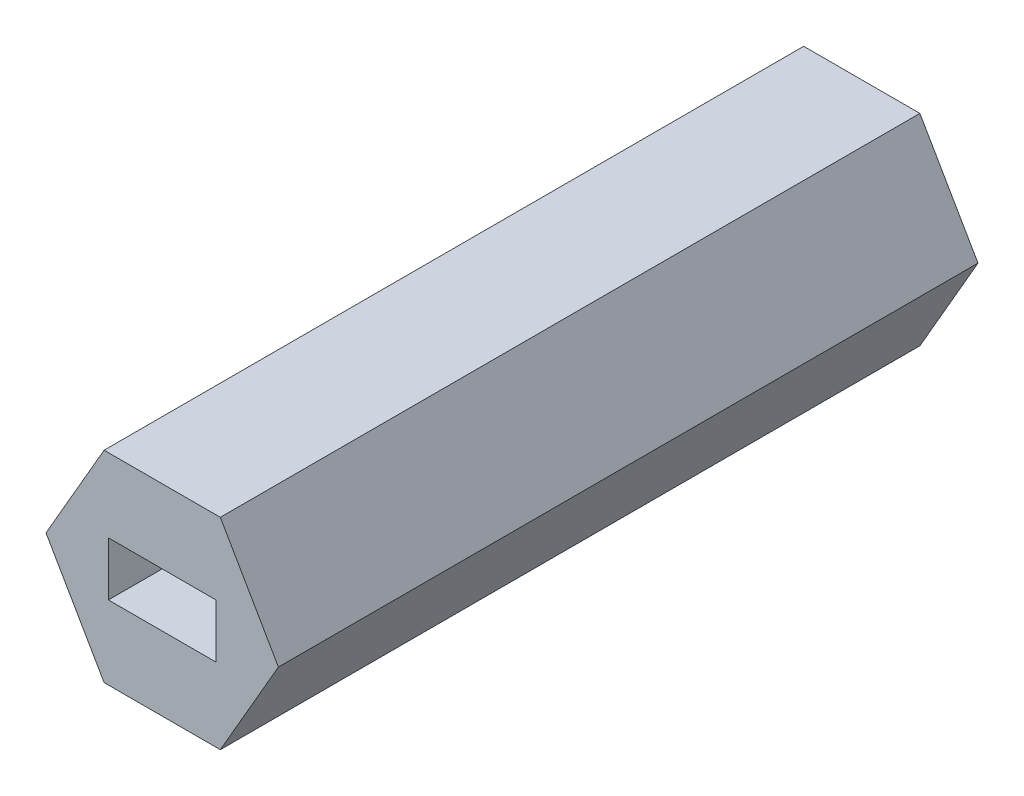
SolidWorks part; units mm, degrees
ref_plane "Front Plane" through (0, 0, 0) normal (0, 0, 1) x (1, 0, 0)
ref_plane "Top Plane" through (0, 0, 0) normal (0, 1, 0) x (1, 0, 0)
ref_plane "Right Plane" through (0, 0, 0) normal (1, 0, 0) x (0, 0, -1)
sketch "Sketch1" plane through (0, 0, 0) normal (0, 0, 1) x (1, 0, 0)
  line L1 (-2.7424, 4.75) -> (-5.4848, 0)
  line L2 (-5.4848, 0) -> (-2.7424, -4.75)
  line L3 (-2.7424, -4.75) -> (2.7424, -4.75)
  line L4 (2.7424, -4.75) -> (5.4848, 0)
  line L5 (5.4848, 0) -> (2.7424, 4.75)
  line L6 (2.7424, 4.75) -> (-2.7424, 4.75)
  line L7 (2.54, -1.27) -> (-2.54, -1.27)
  line L8 (2.54, -1.27) -> (2.54, 1.27)
  line L9 (2.54, 1.27) -> (-2.54, 1.27)
  line L10 (-2.54, -1.27) -> (-2.54, 1.27)
  line L11 (2.54, -1.27) -> (-2.54, 1.27) construction
  line L12 (2.54, 1.27) -> (-2.54, -1.27) construction
  circle A0 centre (0, 0) radius 4.75 construction
  point P13 (0, 0)
  dimension "D1" = 9.5
  dimension "D2" = 2.54
  dimension "D3" = 5.08
extrude "Boss-Extrude1" add sketch "Sketch1" along normal blind 33.02
